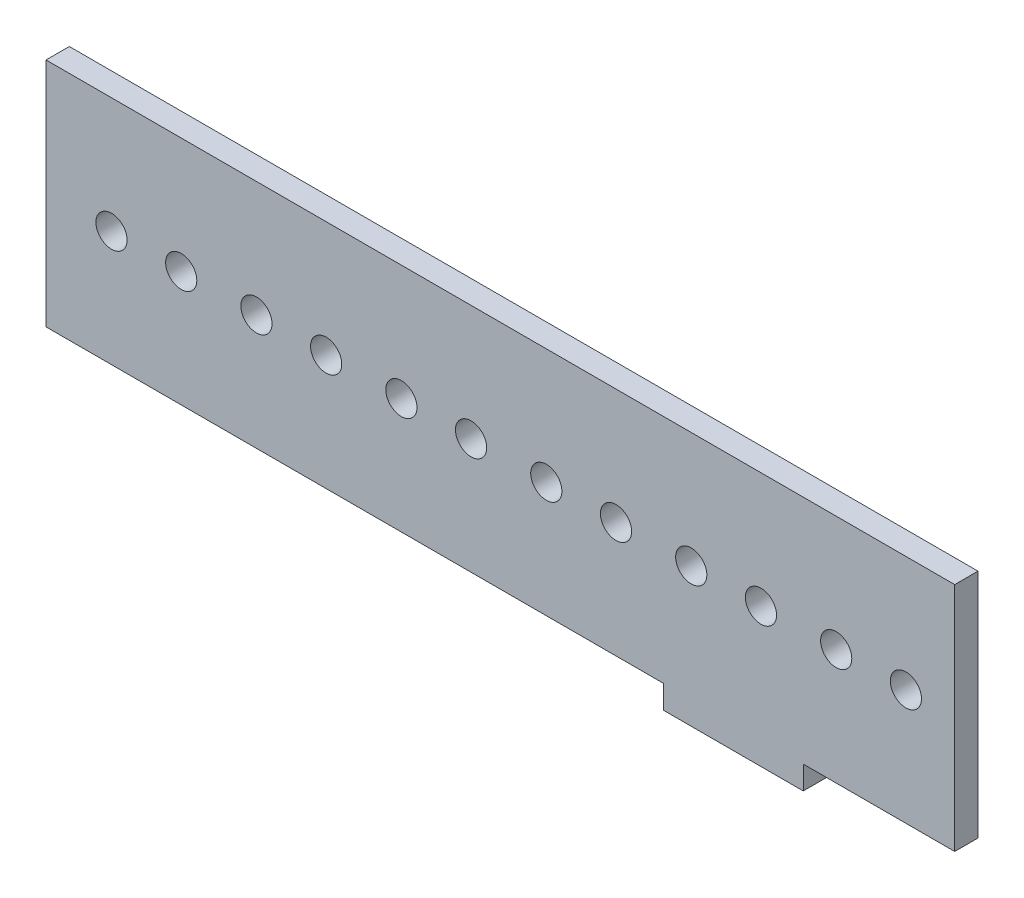
SolidWorks part; units mm, degrees
ref_plane "Front Plane" through (0, 0, 0) normal (0, 0, 1) x (1, 0, 0)
ref_plane "Top Plane" through (0, 0, 0) normal (0, 1, 0) x (1, 0, 0)
ref_plane "Right Plane" through (0, 0, 0) normal (1, 0, 0) x (0, 0, -1)
sketch "Model" plane through (0, 0, 0) normal (0, 0, 1) x (1, 0, 0)
  line L0 (82.55, -37.85) -> (82.55, -31.5)
  line L1 (44.45, -37.85) -> (82.55, -37.85)
  line L2 (44.45, -31.5) -> (44.45, -37.85)
  line L3 (44.45, -31.5) -> (-123.825, -31.5)
  line L4 (-123.825, -31.5) -> (-123.825, 31.5)
  line L5 (123.825, 31.5) -> (123.825, -31.5)
  line L6 (-123.825, 31.5) -> (123.825, 31.5)
  line L7 (123.825, -31.5) -> (82.55, -31.5)
  circle A0 centre (-105.975, 0) radius 4.25
  circle A1 centre (-66.475, 0) radius 4.25
  circle A2 centre (-26.975, 0) radius 4.25
  circle A3 centre (12.525, 0) radius 4.25
  circle A4 centre (-86.975, 0) radius 4.25
  circle A5 centre (-47.475, 0) radius 4.25
  circle A6 centre (-7.975, 0) radius 4.25
  circle A7 centre (31.525, 0) radius 4.25
  circle A8 centre (91.525, 0) radius 4.25
  circle A9 centre (110.525, 0) radius 4.25
  circle A10 centre (71.025, 0) radius 4.25
  circle A11 centre (52.025, 0) radius 4.25
  text T0 "SOLIDWORKS Educational Product." font "SWTXT" height 4.8336
  text T1 "For Instructional Use Only." font "SWTXT" height 4.8336
sketch "Sketch3" plane through (0, 0, 0) normal (0, 0, 1) x (1, 0, 0)
  line L0 (123.825, 31.5) -> (123.825, -31.5) construction
  line L1 (123.825, -31.5) -> (82.55, -31.5) construction
  line L2 (82.55, -37.85) -> (82.55, -31.5) construction
  line L3 (44.45, -31.5) -> (44.45, -37.85) construction
  line L4 (44.45, -37.85) -> (82.55, -37.85) construction
  line L5 (44.45, -31.5) -> (-123.825, -31.5) construction
  line L6 (-123.825, 31.5) -> (123.825, 31.5) construction
  line L7 (-123.825, -31.5) -> (-123.825, 31.5) construction
  line L8 (123.825, 31.5) -> (123.825, -31.5)
  line L9 (123.825, -31.5) -> (82.55, -31.5)
  line L10 (82.55, -37.85) -> (82.55, -31.5)
  line L11 (44.45, -31.5) -> (44.45, -37.85)
  line L12 (44.45, -37.85) -> (82.55, -37.85)
  line L13 (44.45, -31.5) -> (-123.825, -31.5)
  line L14 (-123.825, 31.5) -> (123.825, 31.5)
  line L15 (-123.825, -31.5) -> (-123.825, 31.5)
  circle A0 centre (-105.975, 0) radius 4.25 construction
  circle A1 centre (-86.975, 0) radius 4.25 construction
  circle A2 centre (-66.475, 0) radius 4.25 construction
  circle A3 centre (-47.475, 0) radius 4.25 construction
  circle A4 centre (-26.975, 0) radius 4.25 construction
  circle A5 centre (-7.975, 0) radius 4.25 construction
  circle A6 centre (12.525, 0) radius 4.25 construction
  circle A7 centre (31.525, 0) radius 4.25 construction
  circle A8 centre (52.025, 0) radius 4.25 construction
  circle A9 centre (71.025, 0) radius 4.25 construction
  circle A10 centre (91.525, 0) radius 4.25 construction
  circle A11 centre (110.525, 0) radius 4.25 construction
  circle A12 centre (-105.975, 0) radius 4.25
  circle A13 centre (-86.975, 0) radius 4.25
  circle A14 centre (-66.475, 0) radius 4.25
  circle A15 centre (-47.475, 0) radius 4.25
  circle A16 centre (-26.975, 0) radius 4.25
  circle A17 centre (-7.975, 0) radius 4.25
  circle A18 centre (12.525, 0) radius 4.25
  circle A19 centre (31.525, 0) radius 4.25
  circle A20 centre (52.025, 0) radius 4.25
  circle A21 centre (71.025, 0) radius 4.25
  circle A22 centre (91.525, 0) radius 4.25
  circle A23 centre (110.525, 0) radius 4.25
extrude "Boss-Extrude1" add sketch "Sketch3" along normal blind 6.35
